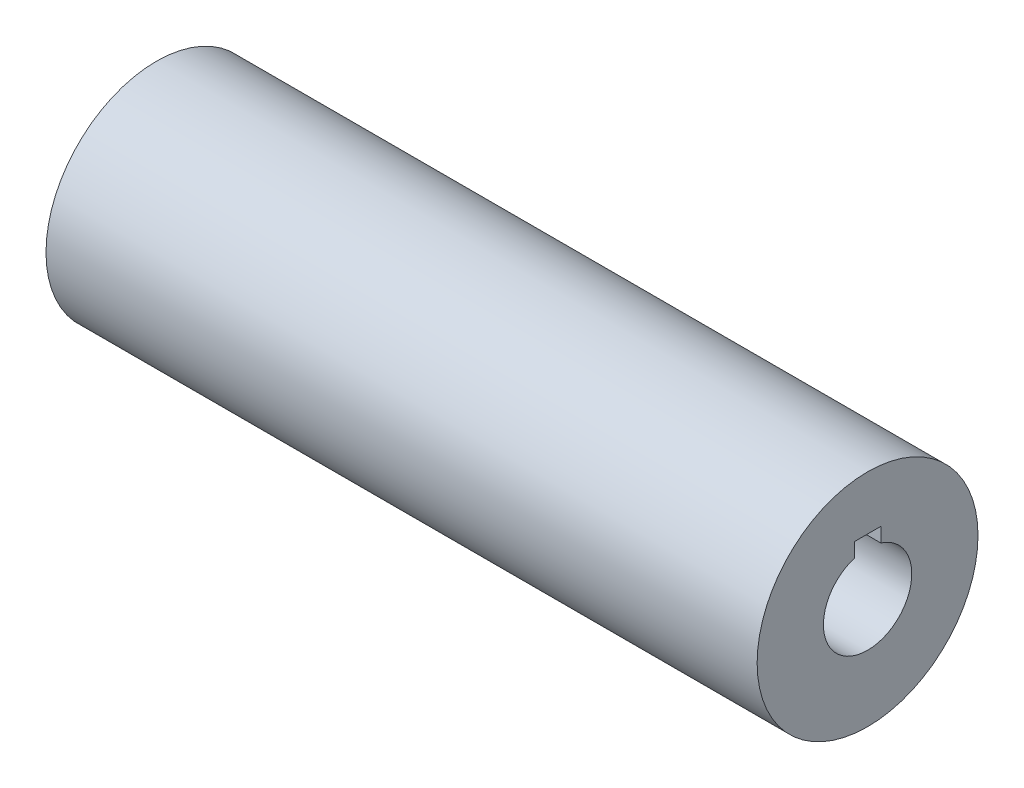
SolidWorks part; units mm, degrees
material "AISI 304"
ref_plane "Ön Düzlem" through (0, 0, 0) normal (0, 0, 1) x (1, 0, 0)
ref_plane "Üst Düzlem" through (0, 0, 0) normal (0, 1, 0) x (1, 0, 0)
ref_plane "Sağ Düzlem" through (0, 0, 0) normal (1, 0, 0) x (0, 0, -1)
sketch "Çizim1" plane through (0, 0, 0) normal (1, 0, 0) x (0, 0, -1)
  circle A0 centre (0, 0) radius 10
  circle A1 centre (0, 0) radius 25
  dimension "D1" = 20
  dimension "D2" = 50
extrude "Yükseklik-Ekstrüzyon1" add sketch "Çizim1" along normal mid plane 161
sketch "Çizim3" plane through (0, 0, 0) normal (1, 0, 0) x (0, 0, -1)
  line L1 (-3, 7.2) -> (3, 7.2)
  line L2 (-3, 7.2) -> (-3, 12.8)
  line L3 (-3, 12.8) -> (3, 12.8)
  line L4 (3, 7.2) -> (3, 12.8)
  line L5 (-3, 7.2) -> (3, 12.8) construction
  line L6 (-3, 12.8) -> (3, 7.2) construction
  circle A0 centre (0, 0) radius 10 construction
  point P0 (0, 10)
  dimension "D1" = 6
  dimension "D2" = 2.8
extrude "Kes-Ekstrüzyon1" cut sketch "Çizim3" against normal mid plane 161 contours L2 L3 L4 L1
